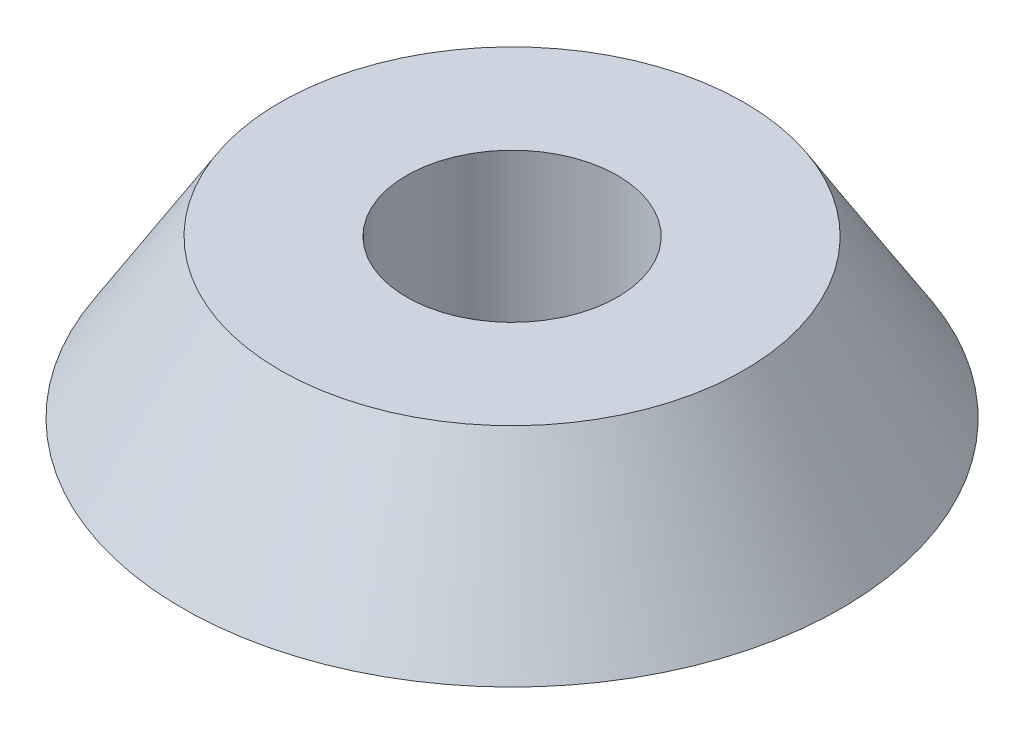
SolidWorks part; units mm, degrees
ref_plane "前视基准面" through (0, 0, 0) normal (0, 0, 1) x (1, 0, 0)
ref_plane "上视基准面" through (0, 0, 0) normal (0, 1, 0) x (1, 0, 0)
ref_plane "右视基准面" through (0, 0, 0) normal (1, 0, 0) x (0, 0, -1)
sketch "草图1" plane through (0, 0, 0) normal (0, 0, 1) x (1, 0, 0)
  line L0 (0, 0) -> (3.25, 0) construction
  line L1 (3.25, 0) -> (3.25, 5)
  line L2 (3.25, 5) -> (0, 5) construction
  line L3 (3.25, 5) -> (7.15, 5)
  line L4 (3.25, 0) -> (10.25, 0)
  line L5 (7.15, 5) -> (10.25, 0)
  line L6 (0, 0) -> (0, 4.9299) construction
  dimension "D1" = 3.25
  dimension "D2" = 5
  dimension "D3" = 3.9
  dimension "8" = 7
revolve "旋转1" add sketch "草图1" angle 360 about L6
sketch "草图2" plane through (0, 0, 0) normal (0, -1, 0) x (1, 0, 0)
  circle A0 centre (0, 0) radius 3.25 construction
  circle A1 centre (0, 0) radius 10.25
  circle A2 centre (0, 0) radius 10.25
  circle A3 centre (0, 0) radius 3.25
  dimension "D1" = 0
extrude "切除-拉伸1" cut sketch "草图2" against normal blind 0.15
